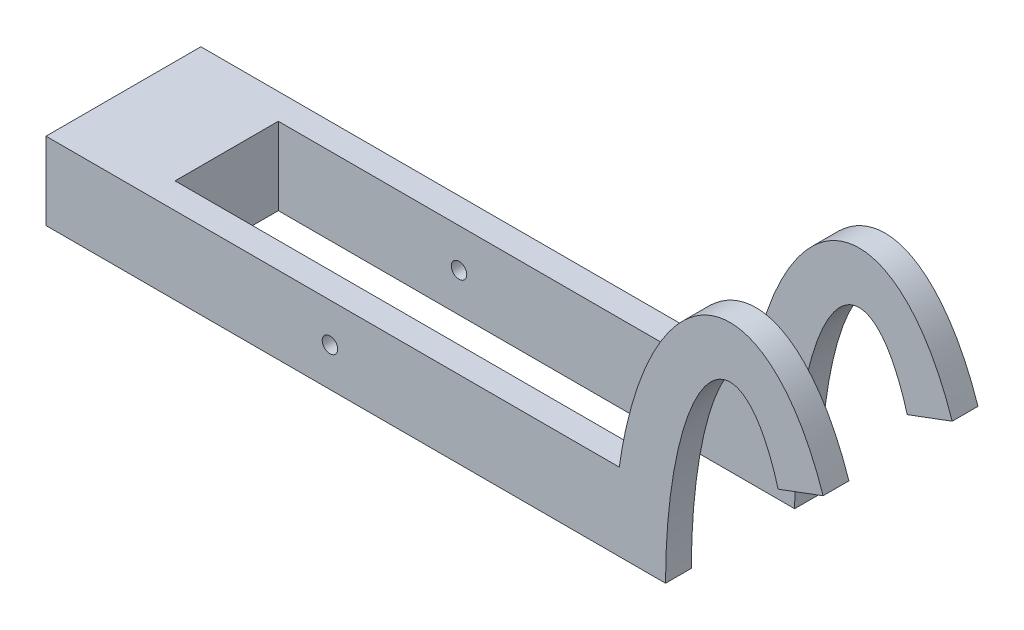
SolidWorks part; units mm, degrees
ref_plane "Front Plane" through (0, 0, 0) normal (0, 0, 1) x (1, 0, 0)
ref_plane "Top Plane" through (0, 0, 0) normal (0, 1, 0) x (1, 0, 0)
ref_plane "Right Plane" through (0, 0, 0) normal (1, 0, 0) x (0, 0, -1)
sketch "Sketch1" plane through (0, 0, 0) normal (0, 0, 1) x (1, 0, 0)
  line L0 (0, 0) -> (0, 19.05)
  line L1 (0, 19.05) -> (141.0162, 19.05)
  line L2 (0, 0) -> (152.4, 0)
  line L3 (180.0982, 33.9) -> (191.1615, 38.0214)
  ellipse E0 centre (168.275, 0) end of major axis (168.275, 50.8) minor radius 15.875 (180.0982, 33.9) -> (152.4, 0) ccw
  ellipse E1 centre (168.275, 0) end of major axis (168.275, 63.5) minor radius 28.575 (191.1615, 38.0214) -> (141.0162, 19.05) ccw
  dimension "D3" = 12.7
  dimension "D4" = 12.7
  dimension "D1" = 152.4
  dimension "D2" = 19.05
  dimension "D5" = 50.8
  dimension "D6" = 31.75
extrude "Boss-Extrude1" add sketch "Sketch1" along normal blind 38.1
sketch "Sketch2" plane through (0, 0, 0) normal (0, -1, 0) x (1, 0, 0)
  line L1 (25.4, 31.75) -> (285.7126, 31.75)
  line L2 (25.4, 31.75) -> (25.4, 6.35)
  line L3 (25.4, 6.35) -> (285.7126, 6.35)
  line L4 (285.7126, 31.75) -> (285.7126, 6.35)
  line L5 (25.4, 19.05) -> (285.7126, 19.05) construction
  line L7 (0, 38.1) -> (0, 0) construction
  point P8 (0, 19.05)
  dimension "D1" = 25.4
  dimension "D2" = 25.4
extrude "Cut-Extrude1" cut sketch "Sketch2" against normal through all
sketch "Sketch3" plane through (0, 0, 38.1) normal (0, 0, 1) x (1, 0, 0)
  line L0 (0, 0) -> (152.4, 0) construction
  line L1 (0, 19.05) -> (0, 0) construction
  circle A0 centre (69.85, 9.525) radius 1.905
  dimension "D1" = 3.81
  dimension "D2" = 9.525
  dimension "D3" = 69.85
extrude "Cut-Extrude2" cut sketch "Sketch3" against normal through all
